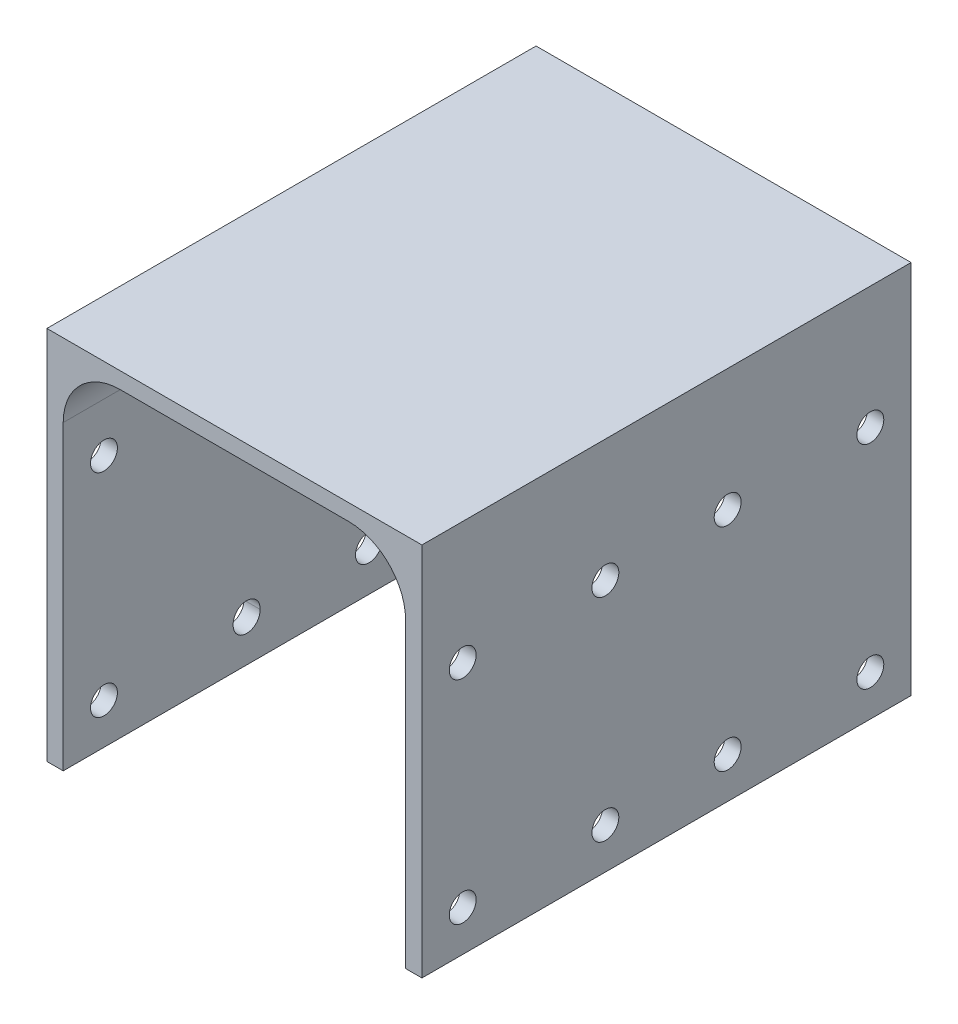
SolidWorks part; units mm, degrees
ref_plane "前视基准面" through (0, 0, 0) normal (0, 0, 1) x (1, 0, 0)
ref_plane "上视基准面" through (0, 0, 0) normal (0, 1, 0) x (1, 0, 0)
ref_plane "右视基准面" through (0, 0, 0) normal (1, 0, 0) x (0, 0, -1)
other "Configuration Table"
ref_plane "基准面1" through (0, -23, 0) normal (0, -1, 0) x (1, 0, 0)
sketch "草图1" plane through (0, -23, 0) normal (0, -1, 0) x (1, 0, 0)
  line L0 (-23, 0) -> (23, 0)
  line L1 (23, 0) -> (23, 60)
  line L2 (23, 60) -> (-23, 60)
  line L3 (-23, 60) -> (-23, 0)
  dimension "D1" = 46
  dimension "D2" = 60
extrude "凸台-拉伸1" add sketch "草图1" against normal blind 46
sketch "草图2" plane through (0, 0, 60) normal (0, 0, 1) x (1, 0, 0)
  line L0 (-21, -23) -> (21, -23)
  line L1 (21, -23) -> (21, 21)
  line L2 (21, 21) -> (-21, 21)
  line L3 (-21, 21) -> (-21, -23)
  line L4 (23, 23) -> (23, -23) construction
  line L5 (23, -23) -> (-23, -23) construction
  dimension "D1" = 2
  dimension "D2" = 44
  dimension "D3" = 44
extrude "切除-拉伸1" cut sketch "草图2" against normal through all
hole_wizard "Ø3.3 (3.3) 直径孔1" positions "草图4" profile "草图3" hole size "Ø3.3" standard "ANSI Metric"
sketch "草图4" plane through (-23, 0, 0) normal (-1, 0, 0) x (0, 0, 1)
  point P0 (55, -18)
  point P1 (22.5, -18)
  point P2 (22.5, 8)
  point P3 (55, 8)
  point P4 (5, 8)
  point P5 (37.5, 8)
  point P6 (37.5, -17.8198)
  point P7 (5, -18)
sketch "草图3" plane through (-23, -18, 55) normal (0, 1, 0) x (0, 0, 1)
  line L0 (0, 0) -> (0, 2)
  line L1 (0, 2) -> (1.65, 2)
  line L2 (1.65, 2) -> (1.65, 0)
  line L5 (1.65, 0) -> (0, 0)
  line L11 (0, -6.35) -> (0, 107.95) construction
  dimension "通孔孔直径" = 3.3
  dimension "通孔孔深度" = 2
hole_wizard "Ø3.3 (3.3) 直径孔2" positions "草图6" profile "草图5" hole size "Ø3.3" standard "ANSI Metric"
sketch "草图6" plane through (23, 0, 0) normal (1, 0, 0) x (0, 0, -1)
  point P0 (-55, 8)
  point P1 (-22.5, 8)
  point P2 (-22.5, -18)
  point P3 (-55, -18)
  point P4 (-5, -18)
  point P5 (-5, 8)
  point P6 (-37.5, 8)
  point P7 (-37.5, -18)
sketch "草图5" plane through (23, 8, 55) normal (0, 1, 0) x (0, 0, -1)
  line L0 (0, 0) -> (0, 46)
  line L1 (0, 46) -> (1.65, 46)
  line L2 (1.65, 46) -> (1.65, 0)
  line L5 (1.65, 0) -> (0, 0)
  line L11 (0, -6.35) -> (0, 107.95) construction
  dimension "通孔孔直径" = 3.3
  dimension "通孔孔深度" = 46
fillet "圆角1" radius 7 2 edges at (-21, 21, 30) (21, 21, 30)
